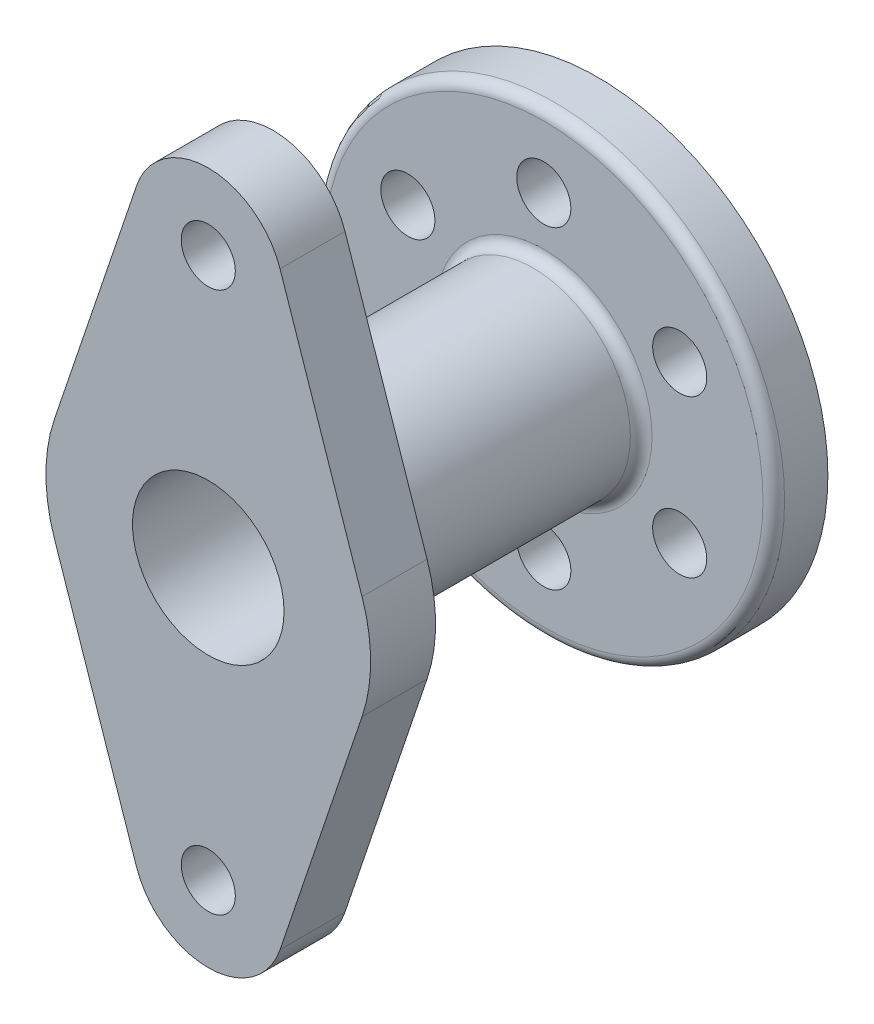
SolidWorks part; units mm, degrees
material "6061 Alloy"
ref_plane "Front Plane" through (0, 0, 0) normal (0, 0, 1) x (1, 0, 0)
ref_plane "Top Plane" through (0, 0, 0) normal (0, 1, 0) x (1, 0, 0)
ref_plane "Right Plane" through (0, 0, 0) normal (1, 0, 0) x (0, 0, -1)
sketch "Sketch1" plane through (0, 0, 0) normal (0, 0, 1) x (1, 0, 0)
  circle A0 centre (0, 0) radius 42.5
  dimension "D1" = 85
extrude "Boss-Extrude1" add sketch "Sketch1" along normal blind 10
sketch "Sketch2" plane through (0, 0, 10) normal (0, 0, 1) x (1, 0, 0)
  circle A0 centre (0, 0) radius 29 construction
  circle A1 centre (0, 29) radius 5
  dimension "D1" = 58
  dimension "D2" = 10
extrude "Cut-Extrude1" cut sketch "Sketch2" against normal through all
pattern_circular "CirPattern2" count 6 over 360 about axis through (0, 0, 0) along (0, 0, 1) of "Cut-Extrude1"
sketch "Sketch3" plane through (0, 0, 10) normal (0, 0, 1) x (1, 0, 0)
  circle A0 centre (0, 0) radius 18
  dimension "D1" = 36
extrude "Boss-Extrude2" add sketch "Sketch3" along normal blind 50
sketch "Sketch4" plane through (0, 0, 60) normal (0, 0, 1) x (1, 0, 0)
  line L0 (0, 50) -> (0, -52.7099) construction
  line L1 (59.4364, 0) -> (-69.0709, 0) construction
  line L2 (-13.2638, 54.48) -> (-28.4225, 9.6)
  line L3 (13.2638, 54.48) -> (28.4225, 9.6)
  line L4 (13.2638, -54.48) -> (28.4225, -9.6)
  line L5 (-13.2638, -54.48) -> (-28.4225, -9.6)
  arc A0 (28.4225, -9.6) -> (28.4225, 9.6) centre (0, 0) ccw
  arc A1 (13.2638, 54.48) -> (-13.2638, 54.48) centre (0, 50) ccw
  arc A2 (13.2638, -54.48) -> (-13.2638, -54.48) centre (0, -50) cw
  arc A3 (-28.4225, 9.6) -> (-28.4225, -9.6) centre (0, 0) ccw
  dimension "D1" = 60
  dimension "D2" = 28
  dimension "D3" = 50
extrude "Boss-Extrude3" add sketch "Sketch4" along normal blind 12
sketch "Sketch5" plane through (0, 0, 72) normal (0, 0, 1) x (1, 0, 0)
  circle A0 centre (0, 50) radius 5
  arc A1 (13.2638, 54.48) -> (-13.2638, 54.48) centre (0, 50) ccw construction
  dimension "D1" = 10
extrude "Cut-Extrude3" cut sketch "Sketch5" against normal through all
mirror "Mirror1" about plane through (0, 0, 0) normal (0, 1, 0) of "Cut-Extrude3"
hole_wizard "CBORE for M2.5 Pan Head Machine Screw1" positions "Sketch6" profile "Sketch7" counterbore size "M2.5" standard "ANSI Metric" end condition through all
sketch "Sketch6" plane through (0, 0, 72) normal (0, 0, 1) x (1, 0, 0)
  point P0 (0, 0)
sketch "Sketch7" plane through (0, 0, 72) normal (1, 0, 0) x (0, -1, 0)
  line L0 (0, 0) -> (0, 72)
  line L1 (0, 72) -> (10, 72)
  line L3 (10, 72) -> (10, 25)
  line L4 (10, 25) -> (14, 25)
  line L5 (14, 25) -> (14, 0)
  line L7 (14, 0) -> (0, 0)
  line L11 (0, -6.35) -> (0, 107.95) construction
  dimension "Thru Hole Dia." = 20
  dimension "Thru Hole Depth" = 72
  dimension "C'Bore Dia." = 28
  dimension "C'Bore Depth" = 25
fillet "Fillet1" radius 2 2 edges at (42.5, 0, 10) (18, 0, 10)
